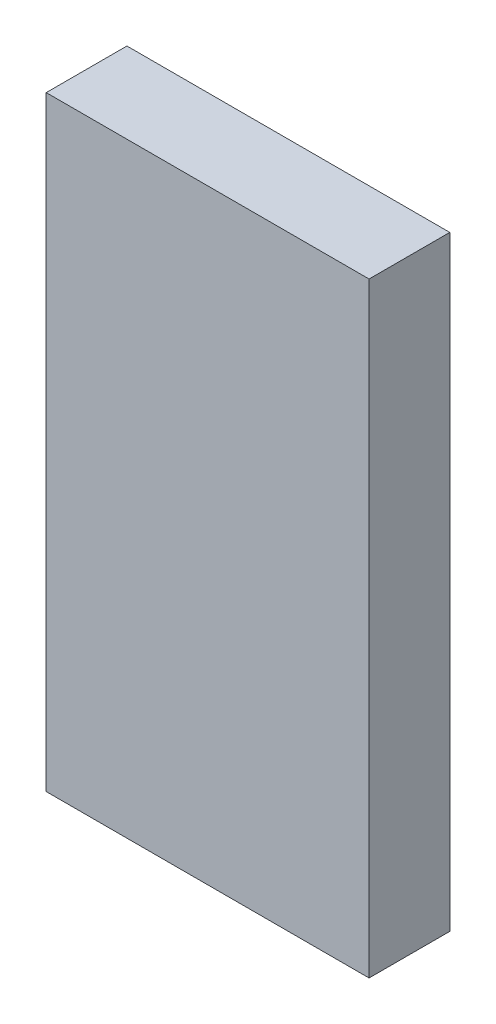
SolidWorks part; units mm, degrees
material "ABS"
ref_plane "Front Plane" through (0, 0, 0) normal (0, 0, 1) x (1, 0, 0)
ref_plane "Top Plane" through (0, 0, 0) normal (0, 1, 0) x (1, 0, 0)
ref_plane "Right Plane" through (0, 0, 0) normal (1, 0, 0) x (0, 0, -1)
sketch "Sketch1" plane through (0, 0, 0) normal (0, 0, 1) x (1, 0, 0)
  line L1 (-4, -7.5) -> (4, -7.5)
  line L2 (-4, -7.5) -> (-4, 7.5)
  line L3 (-4, 7.5) -> (4, 7.5)
  line L4 (4, -7.5) -> (4, 7.5)
  line L5 (-4, -7.5) -> (4, 7.5) construction
  line L6 (-4, 7.5) -> (4, -7.5) construction
  point P0 (0, 0)
  dimension "D1" = 15
  dimension "D2" = 8
extrude "Boss-Extrude1" add sketch "Sketch1" along normal mid plane 2
sketch "Sketch2" plane through (0, 0, -1) normal (0, 0, -1) x (-1, 0, 0)
  line L0 (-4, 7.5) -> (4, 7.5) construction
  line L1 (0, 0) -> (4, 0) construction
  line L2 (4, 7.5) -> (4, -7.5) construction
  circle A0 centre (0, 6) radius 1
  circle A1 centre (0, -6) radius 1
  dimension "D1" = 2
  dimension "D2" = 1.5
extrude "Cut-Extrude1" cut sketch "Sketch2" against normal blind 1
